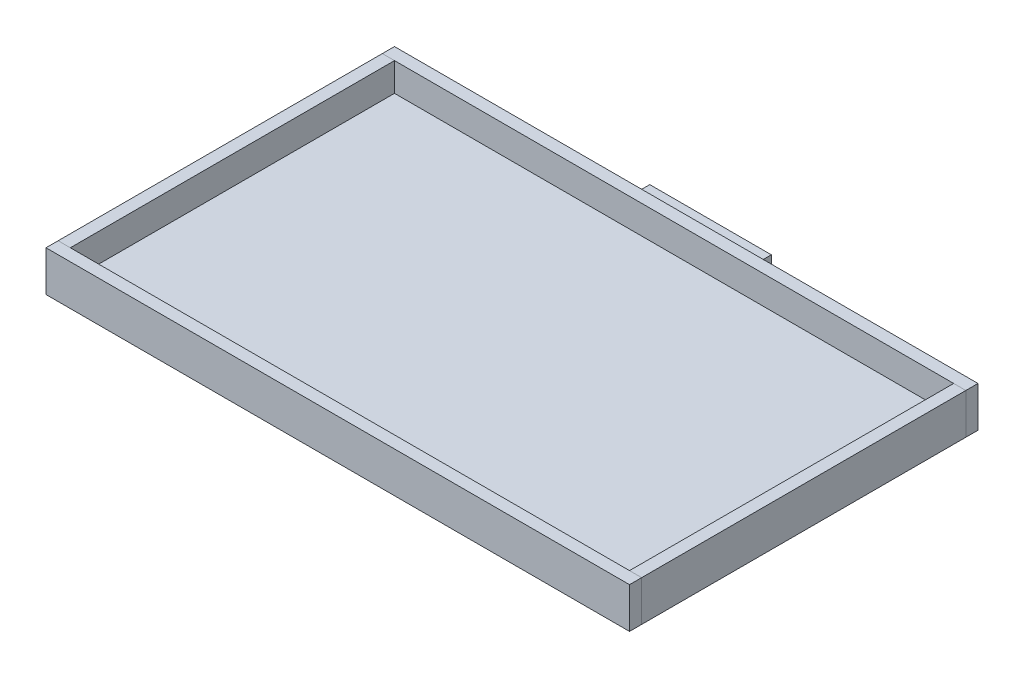
SolidWorks part; units mm, degrees
ref_plane "Front Plane" through (0, 0, 0) normal (0, 0, 1) x (1, 0, 0)
ref_plane "Top Plane" through (0, 0, 0) normal (0, 1, 0) x (1, 0, 0)
ref_plane "Right Plane" through (0, 0, 0) normal (1, 0, 0) x (0, 0, -1)
sketch "Sketch1" plane through (0, 0, 0) normal (0, 1, 0) x (1, 0, 0)
  line L1 (0, 0) -> (876.3, 0)
  line L2 (0, 0) -> (0, 508)
  line L3 (0, 508) -> (876.3, 508)
  line L4 (876.3, 0) -> (876.3, 508)
  dimension "D1" = 876.3
  dimension "D2" = 508
extrude "Boss-Extrude1" add sketch "Sketch1" along normal blind 19.05
sketch "Sketch2" plane through (0, 0, 0) normal (0, 0, 1) x (1, 0, 0)
  line L0 (876.3, 19.05) -> (876.3, 0) construction
  line L1 (-19.05, 0) -> (895.35, 0)
  line L2 (-19.05, 0) -> (-19.05, 63.5)
  line L3 (-19.05, 63.5) -> (895.35, 63.5)
  line L4 (895.35, 0) -> (895.35, 63.5)
  line L5 (0, 19.05) -> (0, 0) construction
  dimension "D1" = 19.05
  dimension "D2" = 63.5
  dimension "D3" = 19.05
extrude "Boss-Extrude2" add sketch "Sketch2" along normal blind 19.05 separate body
ref_plane "Plane1" through (0, 0, -508) normal (0, 0, -1) x (-1, 0, 0)
sketch "Sketch4" plane through (0, 0, -508) normal (0, 0, -1) x (-1, 0, 0)
  line L0 (-876.3, 0) -> (0, 0) construction
  line L1 (-895.35, 0) -> (19.05, 0)
  line L2 (-895.35, 0) -> (-895.35, 63.5)
  line L3 (-895.35, 63.5) -> (19.05, 63.5)
  line L4 (19.05, 0) -> (19.05, 63.5)
  line L5 (0, 19.05) -> (0, 0) construction
  line L7 (-876.3, 19.05) -> (-876.3, 0) construction
  dimension "D1" = 0
  dimension "D2" = 19.05
  dimension "D3" = 19.05
  dimension "D4" = 63.5
extrude "Boss-Extrude3" add sketch "Sketch4" along normal blind 19.05 separate body
sketch "Sketch5" plane through (0, 0, 0) normal (1, 0, 0) x (0, 0, -1)
  line L1 (508, 0) -> (0, 0)
  line L2 (508, 0) -> (508, 63.5)
  line L3 (508, 63.5) -> (0, 63.5)
  line L4 (0, 0) -> (0, 63.5)
  dimension "D1" = 63.5
extrude "Boss-Extrude4" add sketch "Sketch5" against normal blind 19.05 separate body
ref_plane "Plane2" through (876.3, 0, 0) normal (1, 0, 0) x (0, 0, -1)
sketch "Sketch6" plane through (876.3, 0, 0) normal (1, 0, 0) x (0, 0, -1)
  line L1 (0, 0) -> (508, 0)
  line L2 (0, 0) -> (0, 63.5)
  line L3 (0, 63.5) -> (508, 63.5)
  line L4 (508, 0) -> (508, 63.5)
  dimension "D1" = 63.5
extrude "Boss-Extrude5" add sketch "Sketch6" along normal blind 19.05 separate body
ref_plane "Plane3" through (0, 0, -527.05) normal (0, 0, -1) x (-1, 0, 0)
sketch "Sketch7" plane through (0, 0, -527.05) normal (0, 0, -1) x (-1, 0, 0)
  line L0 (19.05, 63.5) -> (-895.35, 63.5) construction
  line L1 (-533.4, 38.1) -> (-342.9, 38.1)
  line L2 (-533.4, 38.1) -> (-533.4, 25.4)
  line L3 (-533.4, 25.4) -> (-342.9, 25.4)
  line L4 (-342.9, 38.1) -> (-342.9, 25.4)
  line L5 (-895.35, 0) -> (19.05, 0) construction
  point P4 (-438.15, 63.5)
  dimension "D1" = 190.5
  dimension "D2" = 95.25
  dimension "D3" = 12.7
  dimension "D4" = 25.4
extrude "Boss-Extrude6" add sketch "Sketch7" along normal blind 38.1
